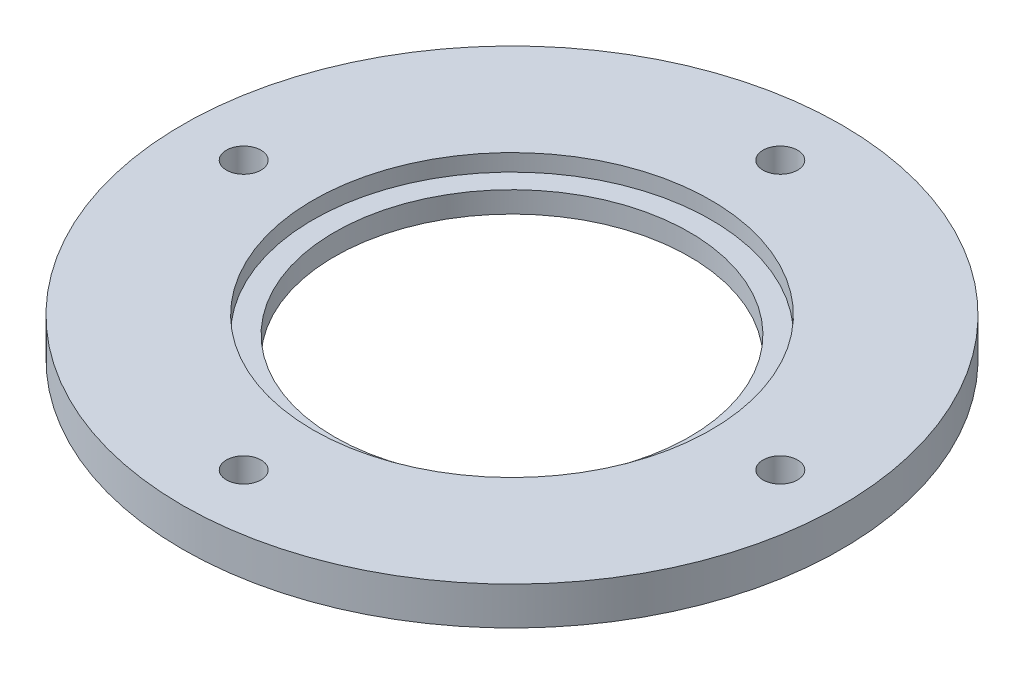
SolidWorks part; units mm, degrees
ref_plane "Front Plane" through (0, 0, 0) normal (0, 0, 1) x (1, 0, 0)
ref_plane "Top Plane" through (0, 0, 0) normal (0, 1, 0) x (1, 0, 0)
ref_plane "Right Plane" through (0, 0, 0) normal (1, 0, 0) x (0, 0, -1)
sketch "Sketch1" plane through (0, 0, 0) normal (0, 1, 0) x (1, 0, 0)
  circle A0 centre (0, 0) radius 39
  dimension "D1" = 78
extrude "Boss-Extrude1" add sketch "Sketch1" along normal blind 4.5
sketch "Sketch2" plane through (0, 4.5, 0) normal (0, 1, 0) x (1, 0, 0)
  line L0 (0, 0) -> (57.3251, 0) construction
  line L1 (0, 0) -> (0, 42.1508) construction
  circle A1 centre (31.75, 0) radius 2.05
  circle A2 centre (0, -31.75) radius 2.05
  circle A3 centre (-31.75, 0) radius 2.05
  circle A4 centre (0, 31.75) radius 2.05
  point P16 (0, 0)
  dimension "D3" = 4.1
  dimension "D2" = 31.75
  dimension "D4" = 4
extrude "Cut-Extrude1" cut sketch "Sketch2" against normal blind 4.5
sketch "Sketch3" plane through (0, 4.5, 0) normal (0, 1, 0) x (1, 0, 0)
  circle A0 centre (0, 0) radius 21
  dimension "D1" = 42
extrude "Cut-Extrude2" cut sketch "Sketch3" against normal blind 4.5
sketch "Sketch4" plane through (0, 4.5, 0) normal (0, 1, 0) x (1, 0, 0)
  circle A0 centre (0, 0) radius 23.55
  dimension "D1" = 47.1
extrude "Cut-Extrude3" cut sketch "Sketch4" against normal blind 2
